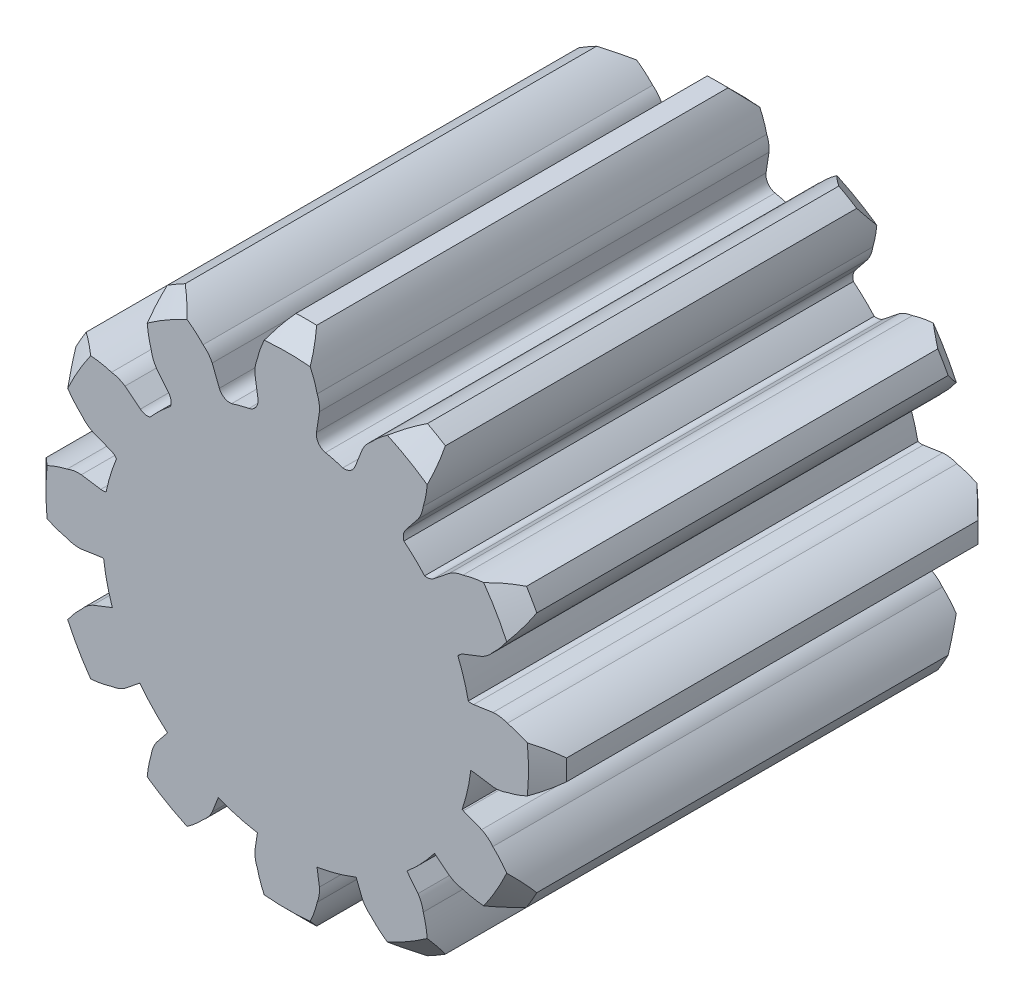
SolidWorks part; units mm, degrees
ref_plane "Front Plane" through (0, 0, 0) normal (0, 0, 1) x (1, 0, 0)
ref_plane "Top Plane" through (0, 0, 0) normal (0, 1, 0) x (1, 0, 0)
ref_plane "Right Plane" through (0, 0, 0) normal (1, 0, 0) x (0, 0, -1)
sketch "Sketch1" plane through (0, 0, 0) normal (0, 0, 1) x (1, 0, 0)
  circle A0 centre (0, 0) radius 4.833
  dimension "Di" = 9.666
extrude "Boss-Extrude1" add sketch "Sketch1" along normal blind 11.7544
sketch "Sketch2" plane through (0, 0, 11.7544) normal (0, 0, 1) x (1, 0, 0)
  line L0 (0, 0) -> (0, 64.154) construction
  line L2 (0.7658, 5.0667) -> (0.8426, 5.5748)
  line L3 (-0.7658, 5.0667) -> (-0.8426, 5.5748)
  line L4 (0.7658, 5.0667) -> (0, 0) construction
  arc A1 (0.0304, 6.7848) -> (0.0304, 6.7848) centre (0, 6) cw construction
  arc A8 (-0.2704, 6.9948) -> (0.2704, 6.9948) centre (0, 0) cw
  circle A9 centre (0, 0) radius 4.833
  arc A11 (1.0004, 4.7283) -> (-1.0004, 4.7283) centre (0, 0) ccw
  arc A17 (0.7287, 6.7627) -> (0.7391, 6.7634) centre (0.7837, 5.9486) ccw construction
  arc A18 (0.7837, 5.9486) -> (0.8426, 5.5748) centre (0.0291, 5.6381) cw
  arc A19 (-1.7749, 5.729) -> (-1.7753, 5.7338) centre (0.7837, 5.9486) ccw construction
  arc A21 (-1.4791, 5.8148) -> (2.2317, 5.5695) centre (0, 0) cw construction
  arc A22 (-4.249, 3.7061) -> (3.5637, 4.369) centre (0, 0) cw construction
  arc A23 (0.7837, 5.9486) -> (0.2704, 6.9948) centre (-1.7182, 5.37) ccw
  arc A24 (1.0004, 4.7283) -> (0.7658, 5.0667) centre (1.0625, 5.0218) cw
  arc A25 (-1.0004, 4.7283) -> (-0.7658, 5.0667) centre (-1.0625, 5.0218) ccw
  arc A26 (-0.7837, 5.9486) -> (-0.8426, 5.5748) centre (-0.0291, 5.6381) ccw
  arc A27 (-0.7837, 5.9486) -> (-0.2704, 6.9948) centre (1.7182, 5.37) cw
  point P0 (0, 0)
  dimension "CT" = 5.6382
  dimension "Dp" = 6
  dimension "De" = 7
  dimension "e" = 0.7854
  dimension "R1" = 0.816
  dimension "R2" = 2.568
  dimension "D2" = 0.3
  dimension "D1" = 0
sketch "Sketch3" plane through (0, 0, 11.7544) normal (0, 0, 1) x (1, 0, 0)
  line L0 (0, 0) -> (335.0525, 5.0373) construction
  point P3 (174.1457, 3.6183)
  point P4 (212.24, 23.1932)
  point P5 (254.7104, 15.8308)
  dimension "M" = 1
  dimension "angulo de presion" = 20
  dimension "Z" = 12
extrude "Boss-Extrude2" add sketch "Sketch2" against normal through all
chamfer "Chamfer1" distance 0.5 angle 45 2 edges at (0, 7, 11.7544) (0, 7, 0)
pattern_circular "CirPattern2" count 12 over 360 about axis through (0, 0.1929, 0) along (0, 0, 1) of "Boss-Extrude2", "Chamfer1"
equation "\"Di@Sketch1\" = 2 * \"Dp@Sketch2\" -  ( 2 * \"M@Sketch3\" * 1.167 ) "
equation "\"D1@Boss-Extrude1\" =  ( 2.15 * pi * \"M@Sketch3\" )  + 5"
equation "\"De@Sketch2\" = \"M@Sketch3\" *  ( \"Z@Sketch3\" + 2 )  / 2"
equation "\"Dp@Sketch2\" = \"M@Sketch3\" * \"Z@Sketch3\" / 2"
equation "\"CT@Sketch2\"=cos ( \"angulo de presion@Sketch3\" )  * \"Dp@Sketch2\""
equation "\"e@Sketch2\"=0.5*\"M@Sketch3\"*pi/2"
equation "\"R1@Sketch2\"=0.068*\"Dp@Sketch2\"*2"
equation "\"R2@Sketch2\"=0.2140*\"Dp@Sketch2\"*2"
equation "\"D2@Sketch2\"=0.3*\"M@Sketch3\""
equation "\"D1@CirPattern2\"=\"Z@Sketch3\""
